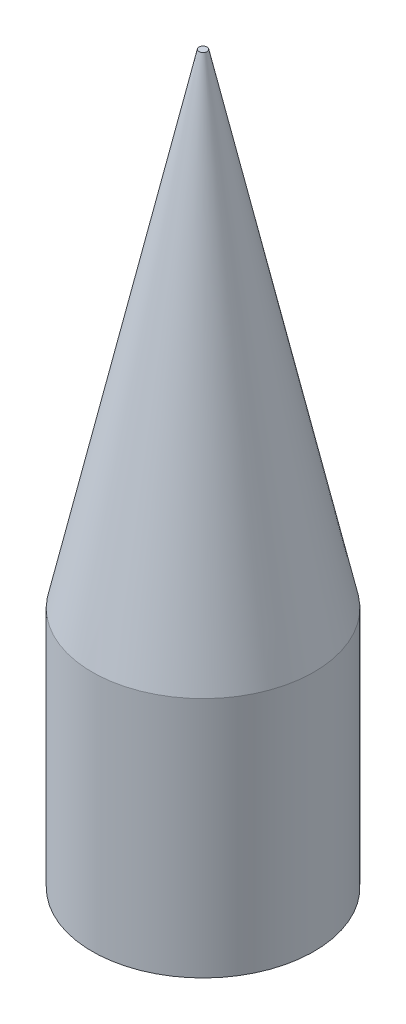
SolidWorks part; units mm, degrees
ref_plane "Front Plane" through (0, 0, 0) normal (0, 0, 1) x (1, 0, 0)
ref_plane "Top Plane" through (0, 0, 0) normal (0, 1, 0) x (1, 0, 0)
ref_plane "Right Plane" through (0, 0, 0) normal (1, 0, 0) x (0, 0, -1)
sketch "Sketch2" plane through (0, 0, 0) normal (0, 0, 1) x (1, 0, 0)
  line L0 (0, 0) -> (0, 120)
  line L2 (27.5, 0) -> (0, 0)
  line L3 (0, 120) -> (1, 120)
  line L4 (1, 120) -> (27.5, 0)
  dimension "D1" = 27.5
  dimension "D2" = 1
  dimension "D3" = 120
revolve "Revolve1" add sketch "Sketch2" angle 360 about L0
sketch "Sketch3" plane through (0, 0, 0) normal (0, -1, 0) x (1, 0, 0)
  circle A0 centre (0, 0) radius 27.5
  circle A1 centre (0, 0) radius 27.5 construction
extrude "Boss-Extrude1" add sketch "Sketch3" along normal blind 60
sketch "Sketch4" plane through (0, -60, 0) normal (0, -1, 0) x (1, 0, 0)
  circle A0 centre (0, 0) radius 25
  dimension "D1" = 50
extrude "Cut-Extrude1" cut sketch "Sketch4" against normal blind 50
